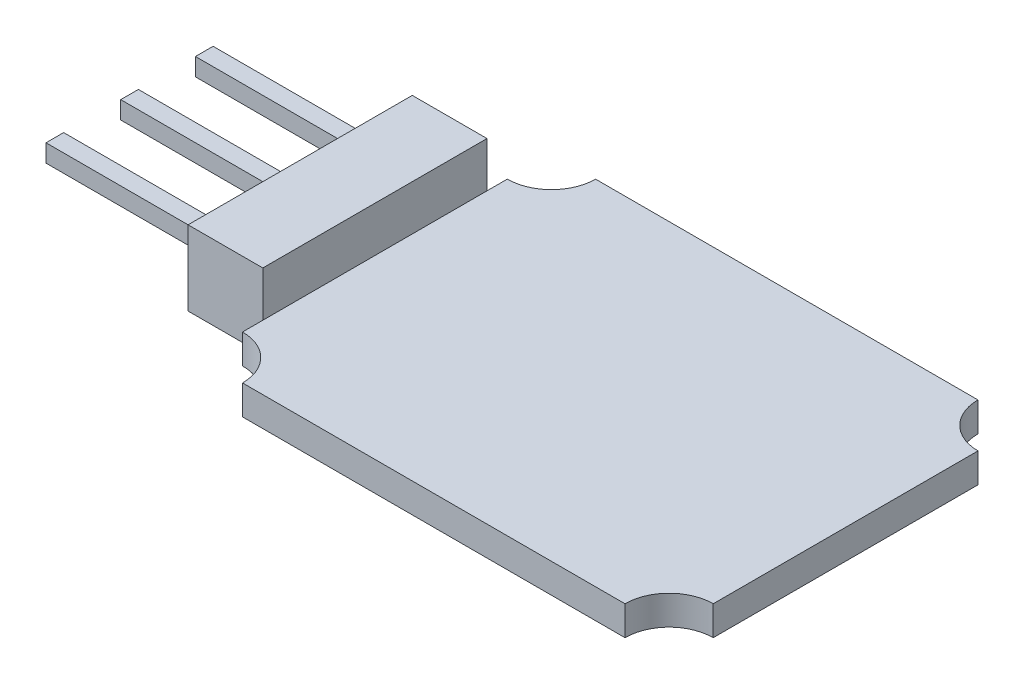
SolidWorks part; units mm, degrees
ref_plane "Plan de face" through (0, 0, 0) normal (0, 0, 1) x (1, 0, 0)
ref_plane "Plan de dessus" through (0, 0, 0) normal (0, 1, 0) x (1, 0, 0)
ref_plane "Plan de droite" through (0, 0, 0) normal (1, 0, 0) x (0, 0, -1)
sketch "Esquisse1" plane through (0, 0, 0) normal (0, 1, 0) x (1, 0, 0)
  line L1 (-6.5, -6) -> (6.5, -6)
  line L2 (-8, -4.5) -> (-8, 4.5)
  line L3 (-6.5, 6) -> (6.5, 6)
  line L4 (8, -4.5) -> (8, 4.5)
  line L5 (-6.8, -5.1) -> (6.8, 5.1) construction
  line L6 (-6.8, 5.1) -> (6.8, -5.1) construction
  arc A0 (-8, 4.5) -> (-6.5, 6) centre (-8, 6) ccw
  arc A1 (6.5, 6) -> (8, 4.5) centre (8, 6) ccw
  arc A2 (8, -4.5) -> (6.5, -6) centre (8, -6) ccw
  arc A3 (-6.5, -6) -> (-8, -4.5) centre (-8, -6) ccw
  point P0 (0, 0)
  dimension "D3" = 3
  dimension "D1" = 12
  dimension "D2" = 16
extrude "Boss.-Extru.1" add sketch "Esquisse1" along normal blind 1
ref_plane "Plan1" through (0, 0, 0) normal (0, 0, -1) x (-1, 0, 0)
sketch "Esquisse2" plane through (0, 0, 0) normal (0, 0, -1) x (-1, 0, 0)
  line L1 (8, 0) -> (10.54, 0)
  line L2 (8, 0) -> (8, 2.54)
  line L3 (8, 2.54) -> (10.54, 2.54)
  line L4 (10.54, 0) -> (10.54, 2.54)
  dimension "D1" = 2.54
  dimension "D2" = 2.54
extrude "Boss.-Extru.2" add sketch "Esquisse2" along normal mid plane 7.62
sketch "Esquisse3" plane through (-10.54, 0, 0) normal (-1, 0, 0) x (0, 0, 1)
  line L0 (-2.24, 0.97) -> (0.3, 0.97) construction
  line L1 (-2.84, 1.57) -> (-2.24, 1.57)
  line L2 (-2.84, 1.57) -> (-2.84, 0.97)
  line L3 (-2.84, 0.97) -> (-2.24, 0.97)
  line L4 (-2.24, 1.57) -> (-2.24, 0.97)
  line L5 (-0.3, 1.57) -> (0.3, 1.57)
  line L6 (-0.3, 1.57) -> (-0.3, 0.97)
  line L7 (-0.3, 0.97) -> (0.3, 0.97)
  line L8 (0.3, 1.57) -> (0.3, 0.97)
  line L9 (2.24, 1.57) -> (2.84, 1.57)
  line L10 (2.24, 1.57) -> (2.24, 0.97)
  line L11 (2.24, 0.97) -> (2.84, 0.97)
  line L12 (2.84, 1.57) -> (2.84, 0.97)
  line L13 (0.3, 0.97) -> (2.84, 0.97) construction
  line L14 (-3.81, 2.54) -> (3.81, 0) construction
  line L15 (-0.3, 0.97) -> (0.3, 1.57) construction
  point P17 (0, 1.27)
  dimension "D1" = 0.6
  dimension "D2" = 2.54
extrude "Boss.-Extru.3" add sketch "Esquisse3" along normal blind 6
chamfer "Chanfrein1" distance 0.2 angle 45 12 edges at (-16.54, 1.57, 2.54) (-16.54, 1.27, 2.84) (-16.54, 0.97, 2.54) (-16.54, 1.27, 2.24) (-16.54, 1.57, 0) (-16.54, 1.27, 0.3) (-16.54, 0.97, 0) (-16.54, 1.27, -0.3) (-16.54, 1.57, -2.54) (-16.54, 1.27, -2.24) (-16.54, 0.97, -2.54) (-16.54, 1.27, -2.84)
